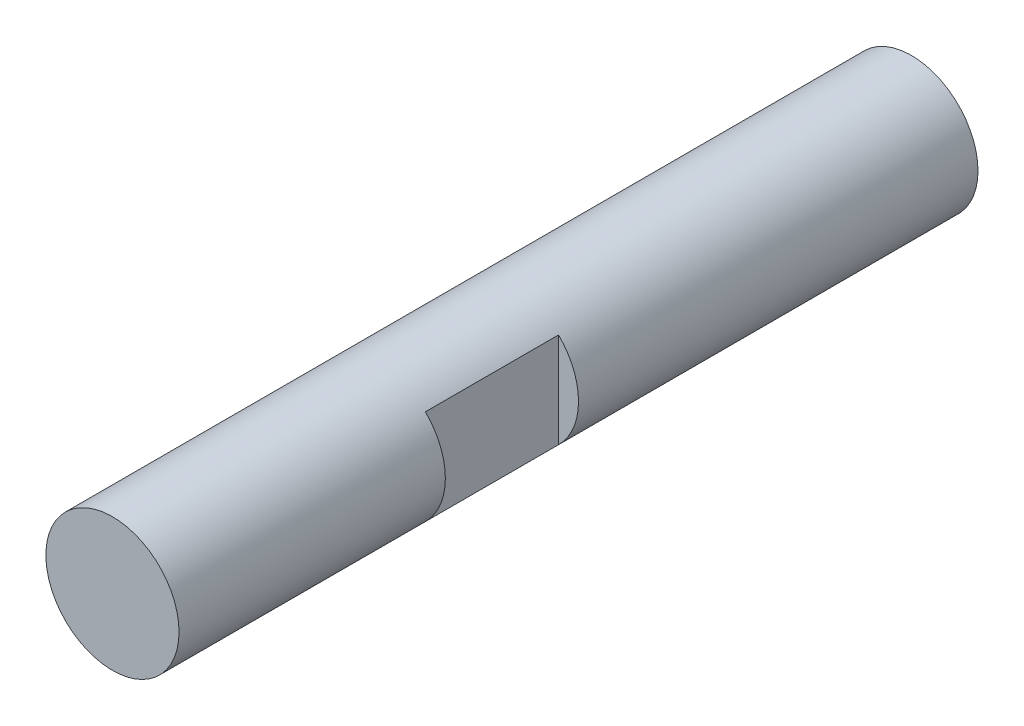
SolidWorks part; units mm, degrees
ref_plane "Front Plane" through (0, 0, 0) normal (0, 0, 1) x (1, 0, 0)
ref_plane "Top Plane" through (0, 0, 0) normal (0, 1, 0) x (1, 0, 0)
ref_plane "Right Plane" through (0, 0, 0) normal (1, 0, 0) x (0, 0, -1)
sketch "Sketch1" plane through (0, 0, 0) normal (0, 0, 1) x (1, 0, 0)
  circle A0 centre (0, 0) radius 6.35
  dimension "D1" = 12.7
extrude "Boss-Extrude1" add sketch "Sketch1" along normal blind 38.1
sketch "Sketch2" plane through (0, 0, 38.1) normal (0, 0, 1) x (1, 0, 0)
  line L0 (-4.445, -4.5348) -> (4.445, -4.5348)
  line L1 (4.445, -4.5348) -> (4.445, 4.5348)
  arc A0 (4.445, 4.5348) -> (-4.445, -4.5348) centre (0, 0) ccw
  circle A1 centre (0, 0) radius 6.35 construction
  dimension "D1" = 4.445
extrude "Boss-Extrude2" add sketch "Sketch2" along normal blind 12.7
sketch "Sketch3" plane through (0, 0, 50.8) normal (0, 0, 1) x (1, 0, 0)
  circle A0 centre (0, 0) radius 6.35
  dimension "D1" = 12.7
extrude "Boss-Extrude3" add sketch "Sketch3" along normal blind 25.4
